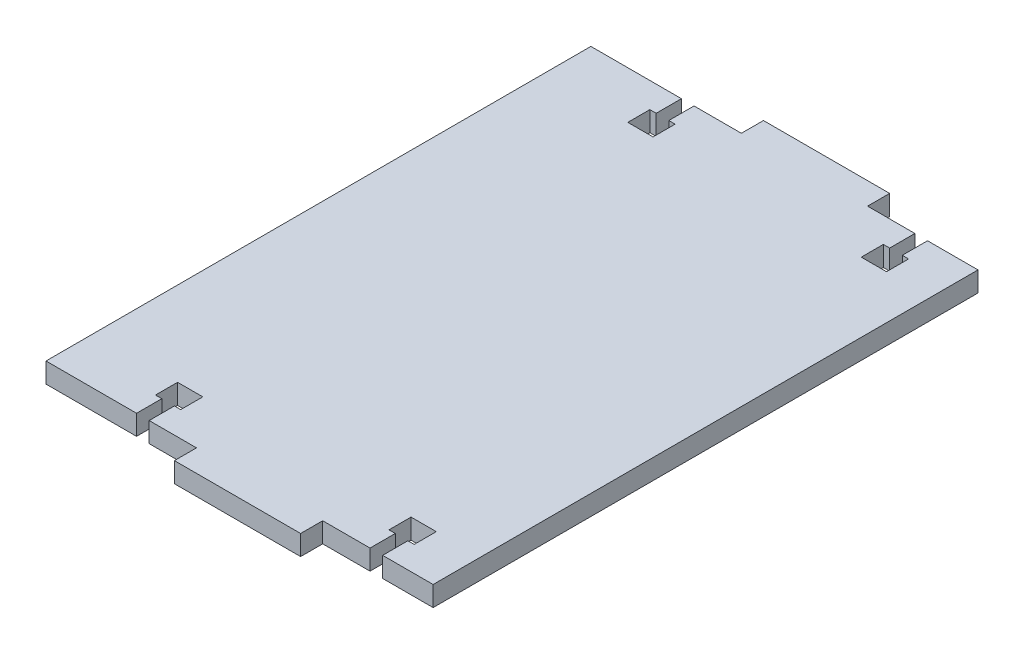
SolidWorks part; units mm, degrees
ref_plane "Front Plane" through (0, 0, 0) normal (0, 0, 1) x (1, 0, 0)
ref_plane "Top Plane" through (0, 0, 0) normal (0, 1, 0) x (1, 0, 0)
ref_plane "Right Plane" through (0, 0, 0) normal (1, 0, 0) x (0, 0, -1)
sketch "Sketch1" plane through (0, 0, 0) normal (0, 1, 0) x (1, 0, 0)
  line L1 (0, 0) -> (61.35, 0)
  line L2 (0, 0) -> (0, 86.35)
  line L3 (0, 86.35) -> (61.35, 86.35)
  line L4 (61.35, 0) -> (61.35, 86.35)
  dimension "D1" = 61.35
  dimension "D2" = 86.35
extrude "Boss-Extrude1" add sketch "Sketch1" along normal blind 3.175
sketch "Sketch2" plane through (0, 0, 0) normal (0, -1, 0) x (1, 0, 0)
  line L0 (0, 0) -> (61.35, 0) construction
  line L1 (0, -86.35) -> (0, 0) construction
  line L2 (23.85, 0) -> (43.85, 0)
  line L3 (23.85, 0) -> (23.85, 3.5)
  line L4 (23.85, 3.5) -> (43.85, 3.5)
  line L5 (43.85, 0) -> (43.85, 3.5)
  dimension "D1" = 20
  dimension "D2" = 3.5
  dimension "D3" = 23.85
extrude "Boss-Extrude2" add sketch "Sketch2" against normal blind 3.175
ref_plane "Plane1" through (0, 0, -43.175) normal (0, 0, 1) x (1, 0, 0)
sketch "Sketch3" plane through (0, 3.175, 0) normal (0, 1, 0) x (1, 0, 0)
  line L0 (16.35, 0) -> (16.35, 4)
  line L1 (0, 0) -> (23.85, 0) construction
  line L2 (16.35, 4) -> (17.35, 4)
  line L3 (17.35, 4) -> (17.35, 7.5)
  line L4 (17.35, 7.5) -> (13.35, 7.5)
  line L5 (13.35, 7.5) -> (13.35, 4)
  line L6 (13.35, 4) -> (14.35, 4)
  line L7 (14.35, 4) -> (14.35, 0)
  line L8 (14.35, 0) -> (16.35, 0)
  line L9 (23.85, -3.5) -> (23.85, 0) construction
  dimension "D1" = 4
  dimension "D2" = 2
  dimension "D3" = 4
  dimension "D4" = 3.5
  dimension "D5" = 7.5
extrude "Cut-Extrude1" cut sketch "Sketch3" against normal blind 3.175
ref_plane "Plane2" through (33.85, 0, 0) normal (1, 0, 0) x (0, 0, -1)
mirror "Mirror1" about plane through (33.85, 0, 0) normal (1, 0, 0) of "Cut-Extrude1"
mirror "Mirror2" about plane through (0, 0, -43.175) normal (0, 0, 1) of "Boss-Extrude2", "Mirror1", "Cut-Extrude1"
